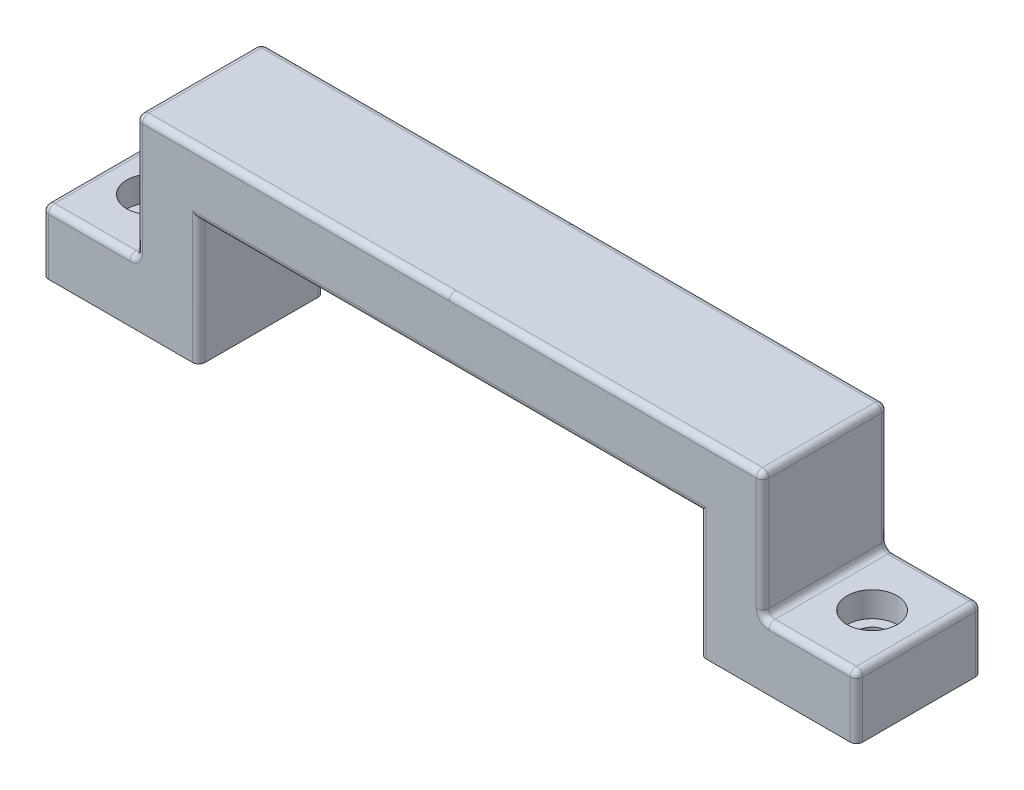
SolidWorks part; units mm, degrees
material "ABS"
ref_plane "Front Plane" through (0, 0, 0) normal (0, 0, 1) x (1, 0, 0)
ref_plane "Top Plane" through (0, 0, 0) normal (0, 1, 0) x (1, 0, 0)
ref_plane "Right Plane" through (0, 0, 0) normal (1, 0, 0) x (0, 0, -1)
sketch "Sketch1" plane through (0, 0, 0) normal (0, 0, 1) x (1, 0, 0)
  line L0 (0, 0) -> (0, 9)
  line L1 (1, 10) -> (14, 10)
  line L2 (15, 11) -> (15, 29)
  line L10 (25, 20) -> (25, 0)
  line L11 (25, 0) -> (0, 0)
  line L12 (16, 30) -> (65, 30)
  line L13 (65, 30) -> (65, 20)
  line L14 (65, 20) -> (25, 20)
  arc A0 (0, 9) -> (1, 10) centre (1, 9) cw
  arc A1 (14, 10) -> (15, 11) centre (14, 11) ccw
  arc A2 (15, 29) -> (16, 30) centre (16, 29) cw
  point P10 (0, 10)
  point P15 (15, 10)
  point P18 (15, 30)
  dimension "D7" = 1
  dimension "D1" = 10
  dimension "D2" = 10
  dimension "D3" = 10
  dimension "D4" = 15
  dimension "D5" = 50
  dimension "D6" = 30
extrude "Boss-Extrude1" add sketch "Sketch1" along normal blind 20
hole_wizard "CBORE for M4 SHCS1" positions "Sketch2" profile "Sketch3" counterbore size "M4" standard "ANSI Metric" end condition through all
sketch "Sketch2" plane through (0, 10, 0) normal (0, 1, 0) x (1, 0, 0)
  line L0 (14, 0) -> (1, 0) construction
  line L1 (1, -20) -> (1, 0) construction
  point P0 (7.5, -10)
  point P7 (7.5, 0)
  point P11 (1, -10)
sketch "Sketch3" plane through (7.5, 10, 10) normal (1, 0, 0) x (0, 0, 1)
  line L0 (0, 0) -> (0, 10)
  line L1 (0, 10) -> (2.35, 10)
  line L3 (2.35, 10) -> (2.35, 4)
  line L4 (2.35, 4) -> (4, 4)
  line L5 (4, 4) -> (4, 0)
  line L7 (4, 0) -> (0, 0)
  line L11 (0, -6.35) -> (0, 107.95) construction
  dimension "Thru Hole Dia." = 4.7
  dimension "Thru Hole Depth" = 10
  dimension "C'Bore Dia." = 8
  dimension "C'Bore Depth" = 4
fillet "Fillet1" radius 1 18 edges at (0, 4.5, 0) (0.2929, 9.7071, 0) (7.5, 10, 0) (14.7071, 10.2929, 0) (15, 20, 0) (15.2929, 29.7071, 0) (0, 4.5, 20) (0.2929, 9.7071, 20) (7.5, 10, 20) (14.7071, 10.2929, 20) (15, 20, 20) (15.2929, 29.7071, 20) (45, 20, 0) (25, 10, 0) (25, 10, 20) (45, 20, 20) (40.5, 30, 0) (40.5, 30, 20)
mirror "Mirror1" about plane through (65, 30, 20) normal (-1, 0, 0) of "Boss-Extrude1", "CBORE for M4 SHCS1", "Fillet1"
